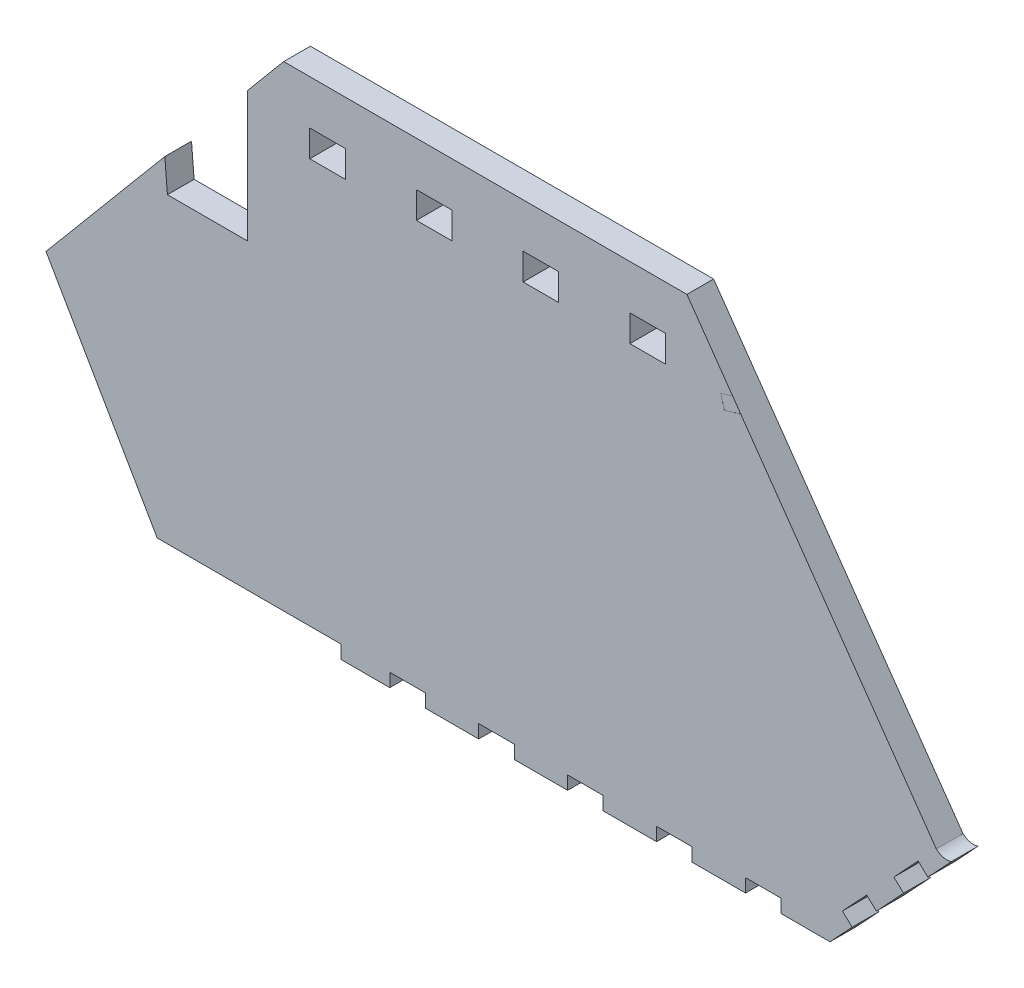
SolidWorks part; units mm, degrees
ref_plane "Plan de face" through (0, 0, 0) normal (0, 0, 1) x (1, 0, 0)
ref_plane "Plan de dessus" through (0, 0, 0) normal (0, 1, 0) x (1, 0, 0)
ref_plane "Plan de droite" through (0, 0, 0) normal (1, 0, 0) x (0, 0, -1)
sketch "Esquisse1" plane through (0, 0, 0) normal (0, 0, 1) x (1, 0, 0)
  line L0 (0, 0) -> (110, 0)
  line L1 (110, 0) -> (137.2799, 29.2541)
  line L2 (137.2799, 29.2541) -> (105.119, 134.4477)
  line L3 (0, 0) -> (0, 3)
  line L4 (0, 3) -> (108.6956, 3)
  line L5 (108.6956, 3) -> (133.9046, 30.0334)
  line L6 (105.119, 134.4477) -> (102.2501, 133.5706)
  line L7 (102.2501, 133.5706) -> (133.9046, 30.0334)
  dimension "D1" = 133
  dimension "D2" = 120
  dimension "D3" = 40
  dimension "D4" = 110
  dimension "D5" = 110
  dimension "D6" = 3
  dimension "D7" = 3
extrude "Boss.-Extru.1" add sketch "Esquisse1" along normal blind 6
sketch "Esquisse3" plane through (0, 0, 0) normal (0, 0, -1) x (-1, 0, 0)
  line L0 (0, 0) -> (-110, 0) construction
  line L1 (-11, 0) -> (-19, 0)
  line L2 (-11, 0) -> (-11, 3)
  line L3 (-11, 3) -> (-19, 3)
  line L4 (-19, 0) -> (-19, 3)
  line L5 (-108.6956, 3) -> (0, 3) construction
  line L6 (-31, 0) -> (-39, 0)
  line L7 (-31, 0) -> (-31, 3)
  line L8 (-31, 3) -> (-39, 3)
  line L9 (-39, 0) -> (-39, 3)
  line L10 (-51, 0) -> (-59, 0)
  line L11 (-51, 0) -> (-51, 3)
  line L12 (-51, 3) -> (-59, 3)
  line L13 (-59, 0) -> (-59, 3)
  line L14 (-71, 0) -> (-79, 0)
  line L15 (-71, 0) -> (-71, 3)
  line L16 (-71, 3) -> (-79, 3)
  line L17 (-79, 0) -> (-79, 3)
  line L18 (-91, 0) -> (-99, 0)
  line L19 (-91, 0) -> (-91, 3)
  line L20 (-91, 3) -> (-99, 3)
  line L21 (-99, 0) -> (-99, 3)
  line L22 (-112.7876, 7.3881) -> (-114.9816, 5.3421)
  line L23 (-112.7876, 7.3881) -> (-118.2435, 13.239)
  line L24 (-114.9816, 5.3421) -> (-120.4376, 11.193)
  line L25 (-118.2435, 13.239) -> (-120.4376, 11.193)
  line L26 (-133.9046, 30.0334) -> (-108.6956, 3) construction
  line L27 (-110, 0) -> (-137.2799, 29.2541) construction
  line L28 (-124.3566, 19.7944) -> (-126.5507, 17.7485)
  line L29 (-124.3566, 19.7944) -> (-129.8126, 25.6453)
  line L30 (-126.5507, 17.7485) -> (-132.0067, 23.5993)
  line L31 (-129.8126, 25.6453) -> (-132.0067, 23.5993)
  line L32 (-107.8052, 115.4008) -> (-110.6741, 116.2779)
  line L33 (-107.8052, 115.4008) -> (-105.4662, 123.0512)
  line L34 (-110.6741, 116.2779) -> (-108.3351, 123.9283)
  line L35 (-105.4662, 123.0512) -> (-108.3351, 123.9283)
  line L36 (-102.2501, 133.5706) -> (-133.9046, 30.0334) construction
  line L37 (-137.2799, 29.2541) -> (-105.119, 134.4477) construction
  line L38 (-105.119, 134.4477) -> (-102.2501, 133.5706) construction
  line L39 (-112.9816, 96.0822) -> (-115.8505, 96.9594)
  line L40 (-112.9816, 96.0822) -> (-110.6426, 103.7327)
  line L41 (-115.8505, 96.9594) -> (-113.5115, 104.6098)
  line L42 (-110.6426, 103.7327) -> (-113.5115, 104.6098)
  line L43 (-118.158, 76.7637) -> (-121.0269, 77.6408)
  line L44 (-118.158, 76.7637) -> (-115.819, 84.4142)
  line L45 (-121.0269, 77.6408) -> (-118.6879, 85.2913)
  line L46 (-115.819, 84.4142) -> (-118.6879, 85.2913)
  line L47 (-123.3343, 57.4452) -> (-126.2033, 58.3223)
  line L48 (-123.3343, 57.4452) -> (-120.9954, 65.0957)
  line L49 (-126.2033, 58.3223) -> (-123.8643, 65.9728)
  line L50 (-120.9954, 65.0957) -> (-123.8643, 65.9728)
  line L51 (-128.5107, 38.1267) -> (-131.3796, 39.0038)
  line L52 (-128.5107, 38.1267) -> (-126.1717, 45.7771)
  line L53 (-131.3796, 39.0038) -> (-129.0407, 46.6543)
  line L54 (-126.1717, 45.7771) -> (-129.0407, 46.6543)
  dimension "D1" = 8
  dimension "D2" = 11
  dimension "D4" = 8
  dimension "D5" = 6
  dimension "D6" = 8
  dimension "D7" = 6
  dimension "D8" = 8
  dimension "D9" = 11
  dimension "D3" = 5
  dimension "D10" = 5
extrude "Enlèv. mat.-Extru.1" cut sketch "Esquisse3" against normal blind 6
sketch "Esquisse4" plane through (0, 0, 0) normal (0, 0, -1) x (-1, 0, 0)
  line L0 (0, 3) -> (-108.6956, 3)
  line L1 (-108.6956, 3) -> (-133.9046, 30.0334)
  line L2 (-133.9046, 30.0334) -> (-102.2501, 133.5706)
  line L3 (-108.6956, 3) -> (41.3044, 3)
  line L4 (41.3044, 3) -> (66.3044, 46.3013)
  line L5 (66.3044, 46.3013) -> (-36.5416, 168.8684)
  line L6 (-36.5416, 168.8684) -> (-133.9046, 30.0334)
  line M4 (-39, 3) -> (-51, 3)
  dimension "D1" = 150
  dimension "D2" = 50
  dimension "D3" = 160
  dimension "D4" = 120
  dimension "D5" = 110
extrude "Boss.-Extru.2" add sketch "Esquisse4" against normal blind 6 contours L5 L6 L1 L0 L3 L4 M4
sketch "Esquisse7" plane through (0, 0, 0) normal (0, 0, -1) x (-1, 0, 0)
  line L0 (-133.9046, 30.0334) -> (-136.0987, 27.9874)
  line L1 (-132.0067, 23.5993) -> (-137.2799, 29.2541) construction
  line L2 (-137.2799, 29.2541) -> (-105.119, 134.4477)
  line L3 (-105.119, 134.4477) -> (-102.2501, 133.5706)
  line L4 (-102.2501, 133.5706) -> (-105.4662, 123.0512) construction
  line L5 (-102.2501, 133.5706) -> (-133.9046, 30.0334)
  arc A0 (-133.9046, 30.0334) -> (-137.2799, 29.2541) centre (-136.2671, 32.5669) cw
extrude "Enlèv. mat.-Extru.2" cut sketch "Esquisse7" against normal blind 6
sketch "Esquisse8" plane through (0, 0, 0) normal (0, 0, -1) x (-1, 0, 0)
  line L0 (12.8549, 110) -> (-77.8252, 110)
  line L1 (66.3044, 46.3013) -> (-36.5416, 168.8684) construction
  line L2 (-36.5416, 168.8684) -> (-133.9046, 30.0334) construction
  line L3 (41.3044, 3) -> (0, 3) construction
  line L4 (12.8549, 110) -> (-36.5416, 168.8684)
  line L5 (-36.5416, 168.8684) -> (-77.8252, 110)
  dimension "D1" = 107
extrude "Enlèv. mat.-Extru.3" cut sketch "Esquisse8" against normal blind 10
sketch "Esquisse9" plane through (0, 0, 6) normal (0, 0, 1) x (1, 0, 0)
  line L0 (-7, 94) -> (-7, 100) construction
  line L1 (73, 100) -> (65, 100)
  line L2 (73, 100) -> (73, 94)
  line L3 (73, 94) -> (65, 94)
  line L4 (65, 100) -> (65, 94)
  line L5 (49, 100) -> (41, 100)
  line L6 (49, 100) -> (49, 94)
  line L7 (49, 94) -> (41, 94)
  line L8 (41, 100) -> (41, 94)
  line L9 (25, 100) -> (17, 100)
  line L10 (25, 100) -> (25, 94)
  line L11 (25, 94) -> (17, 94)
  line L12 (17, 100) -> (17, 94)
  line L13 (1, 100) -> (-7, 100)
  line L14 (1, 100) -> (1, 94)
  line L15 (1, 94) -> (-7, 94)
  line L16 (-7, 100) -> (-7, 94)
extrude "Enlèv. mat.-Extru.4" cut sketch "Esquisse9" against normal blind 6
sketch "Esquisse10" plane through (0, 0, 6) normal (0, 0, 1) x (1, 0, 0)
  line L0 (-21, 71) -> (-21, 100.293)
  line L1 (-66.3044, 46.3013) -> (-12.8549, 110) construction
  line L2 (-21, 71) -> (-21, 109) construction
  line L3 (-21, 100.293) -> (-39.5796, 78.1506)
  line L4 (-39.5796, 78.1506) -> (-39, 71)
  line L5 (-39, 71) -> (-21, 71)
extrude "Enlèv. mat.-Extru.5" cut sketch "Esquisse10" against normal blind 10
sketch "Esquisse11" plane through (0, 0, 6) normal (0, 0, 1) x (1, 0, 0)
  line L0 (86.2712, 91.642) -> (89.9176, 92.7568)
  line L1 (77.8252, 110) -> (133.9046, 30.0334) construction
  line L2 (89.9176, 92.7568) -> (88.106, 95.34)
  line L3 (88.106, 95.34) -> (85.3941, 94.5109)
  line L4 (85.3941, 94.5109) -> (86.2712, 91.642)
  line L5 (168.7861, 120.0064) -> (128.2721, 107.62) construction
extrude "Enlèv. mat.-Extru.6" cut sketch "Esquisse11" against normal blind 0.006
